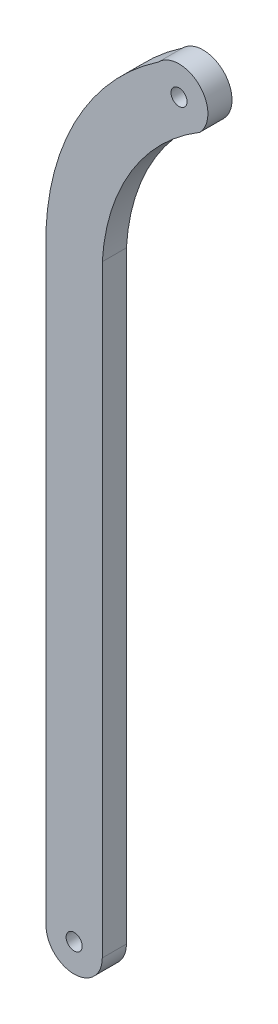
SolidWorks part; units mm, degrees
ref_plane "Plan de face" through (0, 0, 0) normal (0, 0, 1) x (1, 0, 0)
ref_plane "Plan de dessus" through (0, 0, 0) normal (0, 1, 0) x (1, 0, 0)
ref_plane "Plan de droite" through (0, 0, 0) normal (1, 0, 0) x (0, 0, -1)
sketch "Esquisse1" plane through (0, 0, 0) normal (0, 0, 1) x (1, 0, 0)
  line L0 (0, 44.5922) -> (0, -30.4078)
  line L1 (7, -30.4078) -> (7, 44.5922)
  arc A0 (0, -30.4078) -> (7, -30.4078) centre (3.5, -30.4078) ccw
  arc A1 (0, 44.5922) -> (13.9682, 69.5922) centre (31.9577, 43.1387) cw
  arc A2 (7, 44.5922) -> (19.1222, 64.5922) centre (31.9577, 43.1387) cw
  arc A3 (13.9682, 69.5922) -> (19.1222, 64.5922) centre (16.5452, 67.0922) cw
  dimension "D1" = 7
  dimension "D6" = 25
  dimension "D2" = 25
  dimension "D3" = 20
  dimension "D4" = 75
  dimension "D5" = 75
extrude "Boss.-Extru.1" add sketch "Esquisse1" along normal blind 3 contours L1 A2 A3 A1 L0 A0
hole_wizard "Trou de passage d'axe 3/321" positions "Esquisse3D1" profile "Esquisse2" hole size "3/32" standard "PCS" end condition through all
sketch3d "Esquisse3D1"
  line L0 (16.5452, 67.0922, 3) -> (16.5452, 67.0922, 0) construction
  point P0 (16.5452, 67.0922, 3)
sketch "Esquisse2" plane through (16.5452, 67.0922, 3) normal (1, 0, 0) x (0, -1, 0)
  line L0 (0, 0) -> (0, 3)
  line L1 (0, 3) -> (1, 3)
  line L2 (1, 3) -> (1, 0)
  line L5 (1, 0) -> (0, 0)
  line L11 (0, -6.35) -> (0, 107.95) construction
  dimension "Diamètre du perçage jusqu'au prochain" = 2
  dimension "Profondeur du perçage jusqu'au prochain" = 3
hole_wizard "Trou de passage d'axe 3/322" positions "Esquisse3D2" profile "Esquisse3" hole size "3/32" standard "PCS" end condition through all
sketch3d "Esquisse3D2"
  line L0 (3.5, -30.4078, 3) -> (3.5, -30.4078, 0) construction
  point P0 (3.5, -30.4078, 3)
sketch "Esquisse3" plane through (3.5, -30.4078, 3) normal (1, 0, 0) x (0, -1, 0)
  line L0 (0, 0) -> (0, 3)
  line L1 (0, 3) -> (1, 3)
  line L2 (1, 3) -> (1, 0)
  line L5 (1, 0) -> (0, 0)
  line L11 (0, -6.35) -> (0, 107.95) construction
  dimension "Diamètre du perçage jusqu'au prochain" = 2
  dimension "Profondeur du perçage jusqu'au prochain" = 3
